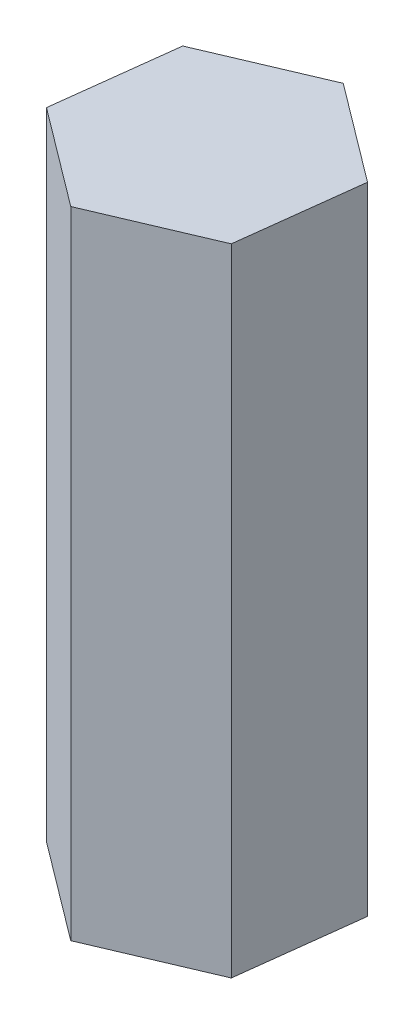
SolidWorks part; units mm, degrees
ref_plane "Front Plane" through (0, 0, 0) normal (0, 0, 1) x (1, 0, 0)
ref_plane "Top Plane" through (0, 0, 0) normal (0, 1, 0) x (1, 0, 0)
ref_plane "Right Plane" through (0, 0, 0) normal (1, 0, 0) x (0, 0, -1)
sketch "Sketch1" plane through (0, 0, 0) normal (0, 1, 0) x (1, 0, 0)
  line L5 (2.3075, -1.7346) -> (2.6559, 1.131)
  line L6 (2.6559, 1.131) -> (0.3485, 2.8656)
  line L7 (0.3485, 2.8656) -> (-2.3075, 1.7346)
  line L8 (-2.3075, 1.7346) -> (-2.6559, -1.131)
  line L9 (-2.6559, -1.131) -> (-0.3485, -2.8656)
  line L10 (-0.3485, -2.8656) -> (2.3075, -1.7346)
  circle A0 centre (0, 0) radius 2.5 construction
  point P1 (0, 0)
extrude "Boss-Extrude1" add sketch "Sketch1" along normal blind 15
